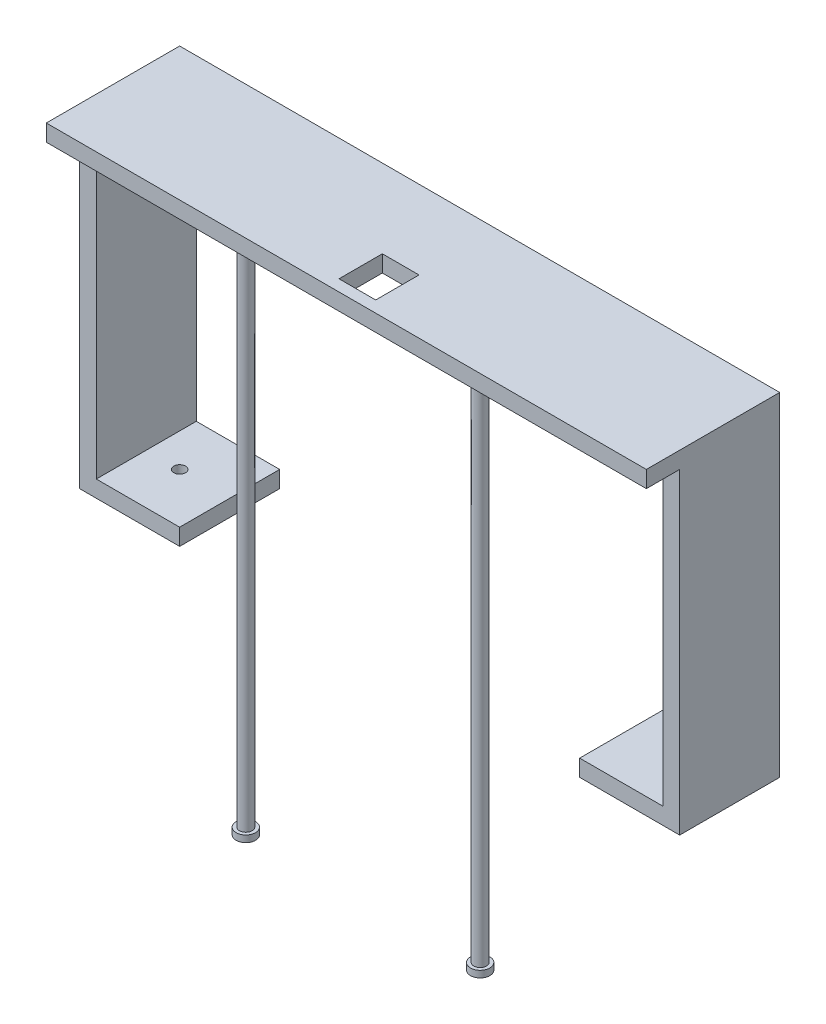
SolidWorks part; units mm, degrees
ref_plane "Front Plane" through (0, 0, 0) normal (0, 0, 1) x (1, 0, 0)
ref_plane "Top Plane" through (0, 0, 0) normal (0, 1, 0) x (1, 0, 0)
ref_plane "Right Plane" through (0, 0, 0) normal (1, 0, 0) x (0, 0, -1)
sketch "Sketch1" plane through (0, 0, 0) normal (0, 0, 1) x (1, 0, 0)
  line L0 (30, 0) -> (0, 0)
  line L1 (0, 0) -> (0, 100)
  line L2 (0, 100) -> (180, 100)
  line L3 (180, 100) -> (180, 0)
  line L4 (180, 0) -> (150, 0)
  line L5 (150, 0) -> (150, 5)
  line L6 (150, 5) -> (175, 5)
  line L7 (175, 5) -> (175, 95)
  line L8 (175, 95) -> (5, 95)
  line L9 (5, 95) -> (5, 5)
  line L10 (5, 5) -> (30, 5)
  line L11 (30, 5) -> (30, 0)
  dimension "D1" = 180
  dimension "D2" = 5
  dimension "D3" = 5
  dimension "D4" = 5
  dimension "D5" = 5
  dimension "D6" = 5
  dimension "D7" = 30
  dimension "D8" = 30
  dimension "D9" = 100
extrude "Boss-Extrude1" add sketch "Sketch1" against normal blind 30
sketch "Sketch2" plane through (0, 0, 0) normal (0, -1, 0) x (1, 0, 0)
  line L0 (0, -30) -> (0, 0) construction
  line L1 (0, 0) -> (30, 0) construction
  line L2 (90, -30) -> (90, -19.425) construction
  line L3 (5, -30) -> (175, -30) construction
  circle A0 centre (15, -15) radius 1.75
  circle A1 centre (165, -15) radius 1.75
  point P4 (0, -15)
  point P8 (15, 0)
  dimension "D1" = 3.5
extrude "Cut-Extrude1" cut sketch "Sketch2" against normal blind 10
sketch "Sketch3" plane through (0, 95, 0) normal (0, -1, 0) x (1, 0, 0)
  line L0 (90, -30) -> (90, 0) construction
  line L1 (5, -30) -> (175, -30) construction
  line L2 (5, 0) -> (175, 0) construction
  circle A0 centre (54.85, 5) radius 1.9
  circle A1 centre (125.15, 5) radius 1.9
  dimension "D1" = 3.8
  dimension "D2" = 35.15
  dimension "D3" = 5
extrude "Boss-Extrude2" add sketch "Sketch3" along normal blind 155
sketch "Sketch5" plane through (0, 0, 0) normal (0, 0, 1) x (1, 0, 0)
  line L0 (5, 95) -> (0, 95)
  line L1 (175, 95) -> (180, 95)
  line L12 (30, 0) -> (30, 5)
  line L13 (30, 5) -> (5, 5)
  line L14 (5, 5) -> (5, 95)
  line L15 (5, 95) -> (175, 95)
  line L16 (175, 95) -> (175, 5)
  line L17 (175, 5) -> (150, 5)
  line L18 (150, 5) -> (150, 0)
  line L19 (150, 0) -> (180, 0)
  line L20 (180, 0) -> (180, 100)
  line L21 (180, 100) -> (0, 100)
  line L22 (0, 100) -> (0, 0)
  line L23 (0, 0) -> (30, 0)
  line L24 (30, 0) -> (30, 5)
  line L25 (30, 5) -> (5, 5)
  line L26 (5, 5) -> (5, 95)
  line L27 (5, 95) -> (175, 95)
  line L28 (175, 95) -> (175, 5)
  line L29 (175, 5) -> (150, 5)
  line L30 (150, 5) -> (150, 0)
  line L31 (150, 0) -> (180, 0)
  line L32 (180, 0) -> (180, 100)
  line L33 (180, 100) -> (0, 100)
  line L34 (0, 100) -> (0, 0)
  line L35 (0, 0) -> (30, 0)
  line M16 (5, 95) -> (175, 95)
  line M21 (180, 0) -> (180, 100)
  line M22 (180, 100) -> (0, 100)
  line M23 (0, 100) -> (0, 0)
  dimension "D1" = 0
extrude "Boss-Extrude3" add sketch "Sketch5" along normal blind 10 contours L1 L0 M16 M21 M22 M23
sketch "Sketch6" plane through (0, -60, 0) normal (0, -1, 0) x (1, 0, 0)
  circle A0 centre (54.85, 5) radius 2.9
  circle A1 centre (54.85, 5) radius 1.9
  circle A2 centre (54.85, 5) radius 1.9
  circle A3 centre (125.15, 5) radius 1.9
  circle A4 centre (125.15, 5) radius 1.9
  circle A5 centre (125.15, 5) radius 2.9
  dimension "D1" = 0
  dimension "D2" = 0
  dimension "D3" = 1
extrude "Boss-Extrude4" add sketch "Sketch6" against normal blind 2
sketch "Sketch7" plane through (0, 95, 0) normal (0, -1, 0) x (1, 0, 0)
  line L0 (89.8801, 10) -> (89.8801, -6.4241) construction
  line L1 (84.3801, 6.5759) -> (84.3801, -6.4241)
  line L2 (84.3801, -6.4241) -> (95.3801, -6.4241)
  line L3 (95.3801, 6.5759) -> (95.3801, -6.4241)
  line L4 (84.3801, 6.5759) -> (95.3801, 6.5759)
  dimension "D2" = 13
  dimension "D3" = 11
extrude "Cut-Extrude2" cut sketch "Sketch7" against normal through all
